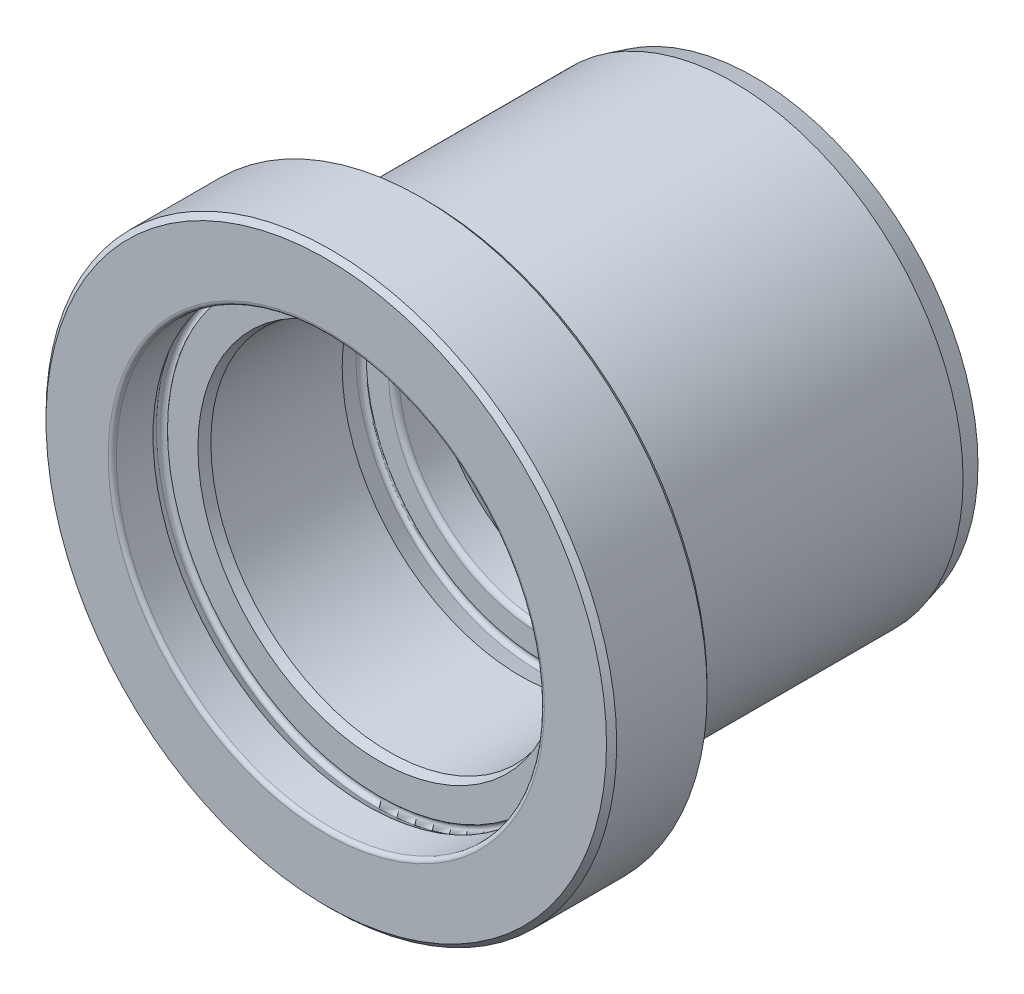
SolidWorks part; units mm, degrees
material "EN39B"
ref_plane "Front" through (0, 0, 0) normal (0, 0, 1) x (1, 0, 0)
ref_plane "Top" through (0, 0, 0) normal (0, 1, 0) x (1, 0, 0)
ref_plane "Right" through (0, 0, 0) normal (1, 0, 0) x (0, 0, -1)
sketch "Sketch1" plane through (0, 0, 0) normal (1, 0, 0) x (0, 0, -1)
  line L0 (0, 0) -> (41.99, 0) construction
  line L1 (0, 27.5025) -> (0, 21.4025)
  line L2 (0.4, 21.0025) -> (4, 21.0025)
  line L3 (4, 21.0025) -> (4.7762, 21.4471)
  line L4 (5.175, 20.7536) -> (5.175, 17.7704)
  line L5 (5.175, 17.7704) -> (6.175, 17.5025)
  line L6 (6.175, 17.5025) -> (19.0656, 17.5025)
  line L7 (19.0656, 17.5025) -> (20.8715, 17.9864)
  line L8 (21.175, 17.2536) -> (21.175, 15.0925)
  line L9 (21.675, 14.5925) -> (24.99, 14.5925)
  line L10 (24.99, 14.5925) -> (26.6199, 15.73)
  line L11 (28.49, 15.6075) -> (37.0475, 15.6075)
  line L12 (37.0475, 15.6075) -> (38.94, 17.5)
  line L13 (0.5, 28.0025) -> (0, 27.5025)
  line L14 (41.99, 19.3375) -> (41.99, 21.9666)
  line L15 (41.99, 21.9666) -> (39.99, 22.5025)
  line L16 (39.99, 22.5025) -> (11.903, 22.5025)
  line L17 (11.903, 22.5025) -> (10.0785, 22.0136)
  line L18 (9.875, 22.7873) -> (9.875, 27.5025)
  line L19 (9.375, 28.0025) -> (0.5, 28.0025)
  line L20 (41.69, 19.0375) -> (39.44, 19.0375)
  line L21 (38.94, 18.5375) -> (38.94, 17.5)
  line L22 (9.875, 27.5025) -> (9.375, 28.0025)
  arc A0 (4.7762, 21.4471) -> (5.175, 20.7536) centre (4.975, 21.1) cw
  arc A1 (20.8715, 17.9864) -> (21.175, 17.2536) centre (20.975, 17.6) cw
  arc A2 (26.6199, 15.73) -> (28.49, 15.6075) centre (27.4783, 14.5) cw
  arc A3 (10.0785, 22.0136) -> (9.875, 22.7873) centre (9.975, 22.4) cw
  arc A4 (21.175, 15.0925) -> (21.675, 14.5925) centre (21.675, 15.0925) ccw
  arc A5 (39.44, 19.0375) -> (38.94, 18.5375) centre (39.44, 18.5375) ccw
  arc A6 (0.4, 21.0025) -> (0, 21.4025) centre (0.4, 21.4025) cw
  arc A7 (41.69, 19.0375) -> (41.99, 19.3375) centre (41.69, 19.3375) ccw
  point P3 (0, 22.5)
  point P4 (-17.5682, 22.5)
  point P5 (-12.7682, 22.5)
  point P6 (-12.7682, 0)
  point P7 (0, 17.5)
  point P9 (-20.8, 17.5)
  point P37 (9.875, 28.0025)
  point P38 (0, 28.0025)
  point P45 (0, 21.0025)
  point P49 (0, 21.0025)
  dimension "D2" = 56.005
  dimension "D8" = 44
  dimension "D9" = 15
  dimension "D12" = 45
  dimension "D13" = 3.05
  dimension "D14" = 29.185
  dimension "D16" = 31.215
  dimension "D6" = 0.4
  dimension "D7" = 0.3
  dimension "D15" = 32
  dimension "D19" = 1.5
  dimension "D22" = 0.4
  dimension "D24" = 0.4
  dimension "D25" = 0.2
  dimension "D26" = 43
  dimension "D27" = 36
  dimension "D35" = 0.5
  dimension "D36" = 0.5
  dimension "D37" = 0.4
  dimension "D38" = 0.3
  dimension "D1" = 41.99
  dimension "D3" = 9.875
  dimension "D4" = 45.005
  dimension "D5" = 15
  dimension "D10" = 2
  dimension "D11" = 38.075
  dimension "D17" = 35
  dimension "D18" = 13.5
  dimension "D20" = 17
  dimension "D21" = 42.005
  dimension "D23" = 0.2
  dimension "D28" = 35.005
  dimension "D29" = 4
  dimension "D30" = 15
  dimension "D31" = 5.175
  dimension "D32" = 21.175
  dimension "D33" = 15
  dimension "D34" = 1
revolve "Revolve1" add sketch "Sketch1" angle 360 about L0
